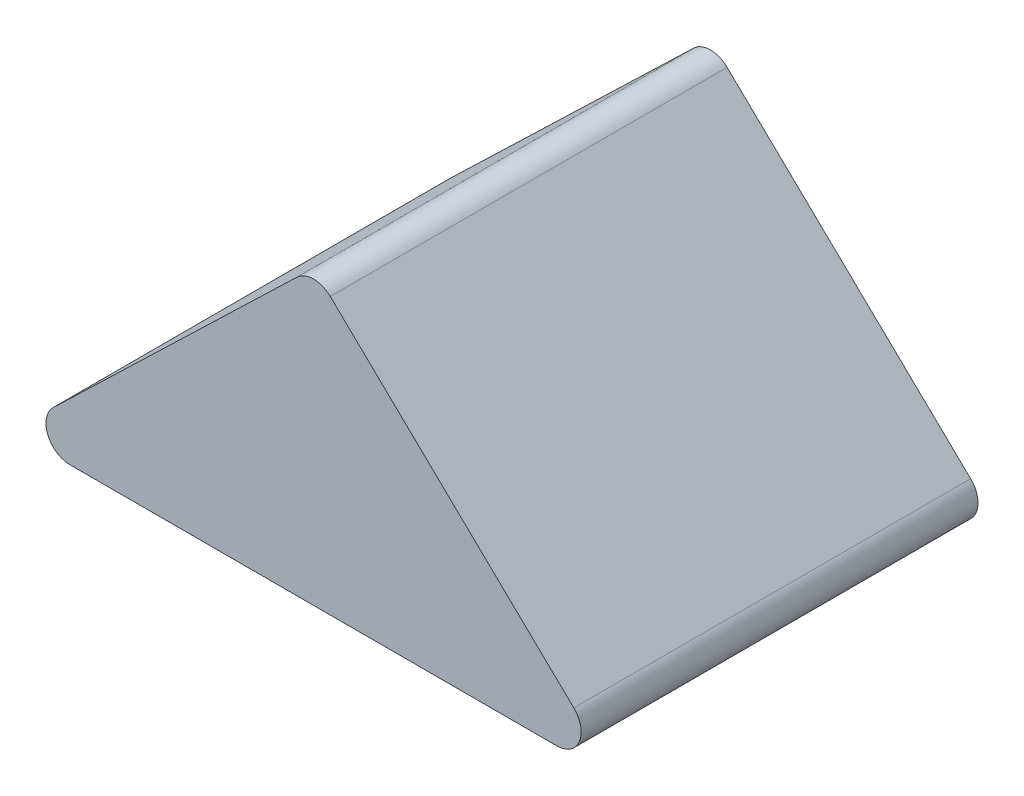
SolidWorks part; units mm, degrees
ref_plane "Front Plane" through (0, 0, 0) normal (0, 0, 1) x (1, 0, 0)
ref_plane "Top Plane" through (0, 0, 0) normal (0, 1, 0) x (1, 0, 0)
ref_plane "Right Plane" through (0, 0, 0) normal (1, 0, 0) x (0, 0, -1)
sketch "Sketch1" plane through (0, 0, 0) normal (0, 0, 1) x (1, 0, 0)
  line L0 (0, 0) -> (40.5, 0)
  line L5 (41.8873, 3.4406) -> (21.6373, 22.9406)
  line L6 (18.8627, 22.9406) -> (-1.3873, 3.4406)
  line L7 (20.25, 23.5) -> (20.25, 0) construction
  line L8 (42.5, 18.0202) -> (42.5, 0) construction
  line L9 (42.5, 0) -> (-2, 0) construction
  line L10 (-2, 0) -> (-2, 20.3688) construction
  arc A2 (41.8873, 3.4406) -> (40.5, 0) centre (40.5, 2) cw
  arc A3 (21.6373, 22.9406) -> (18.8627, 22.9406) centre (20.25, 21.5) ccw
  arc A4 (-1.3873, 3.4406) -> (0, 0) centre (0, 2) ccw
  dimension "D1" = 2
  dimension "D2" = 23.5
  dimension "D3" = 44.5
extrude "Extrude1" add sketch "Sketch1" along normal blind 33
